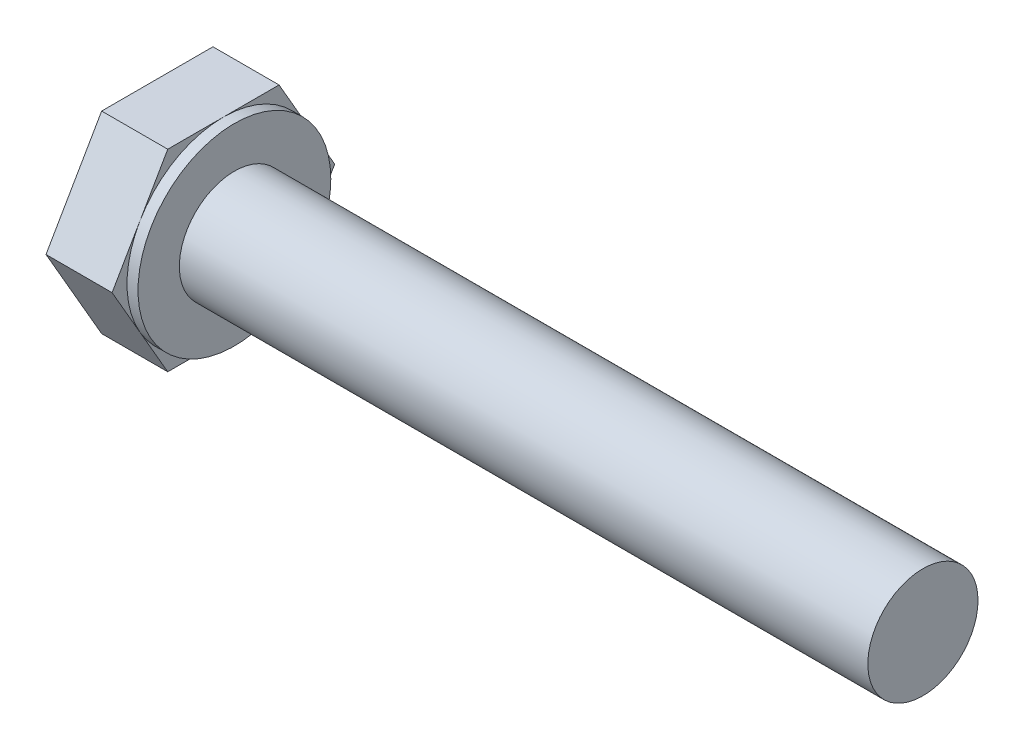
SolidWorks part; units mm, degrees
material "Plain Carbon Steel"
ref_plane "Front Plane" through (0, 0, 0) normal (0, 0, 1) x (1, 0, 0)
ref_plane "Top Plane" through (0, 0, 0) normal (0, 1, 0) x (1, 0, 0)
ref_plane "Right Plane" through (0, 0, 0) normal (1, 0, 0) x (0, 0, -1)
sketch "Sketch1" plane through (0, 0, 0) normal (1, 0, 0) x (0, 0, -1)
  line L1 (-4.0415, 0) -> (-2.0207, -3.5)
  line L2 (-2.0207, -3.5) -> (2.0207, -3.5)
  line L3 (2.0207, -3.5) -> (4.0415, 0)
  line L4 (4.0415, 0) -> (2.0207, 3.5)
  line L5 (2.0207, 3.5) -> (-2.0207, 3.5)
  line L6 (-2.0207, 3.5) -> (-4.0415, 0)
  circle A0 centre (0, 0) radius 3.5 construction
  dimension "D1" = 7
extrude "Boss-Extrude1" add sketch "Sketch1" against normal blind 2.4
sketch "Sketch2" plane through (0, 0, 0) normal (1, 0, 0) x (0, 0, -1)
  line L0 (2.0207, 3.5) -> (-2.0207, 3.5) construction
  circle A0 centre (0, 0) radius 3.5
extrude "Boss-Extrude2" add sketch "Sketch2" along normal blind 0.4
sketch "Sketch3" plane through (0.4, 0, 0) normal (1, 0, 0) x (0, 0, -1)
  circle A0 centre (0, 0) radius 2
  dimension "D1" = 4
extrude "Boss-Extrude3" add sketch "Sketch3" along normal blind 25
